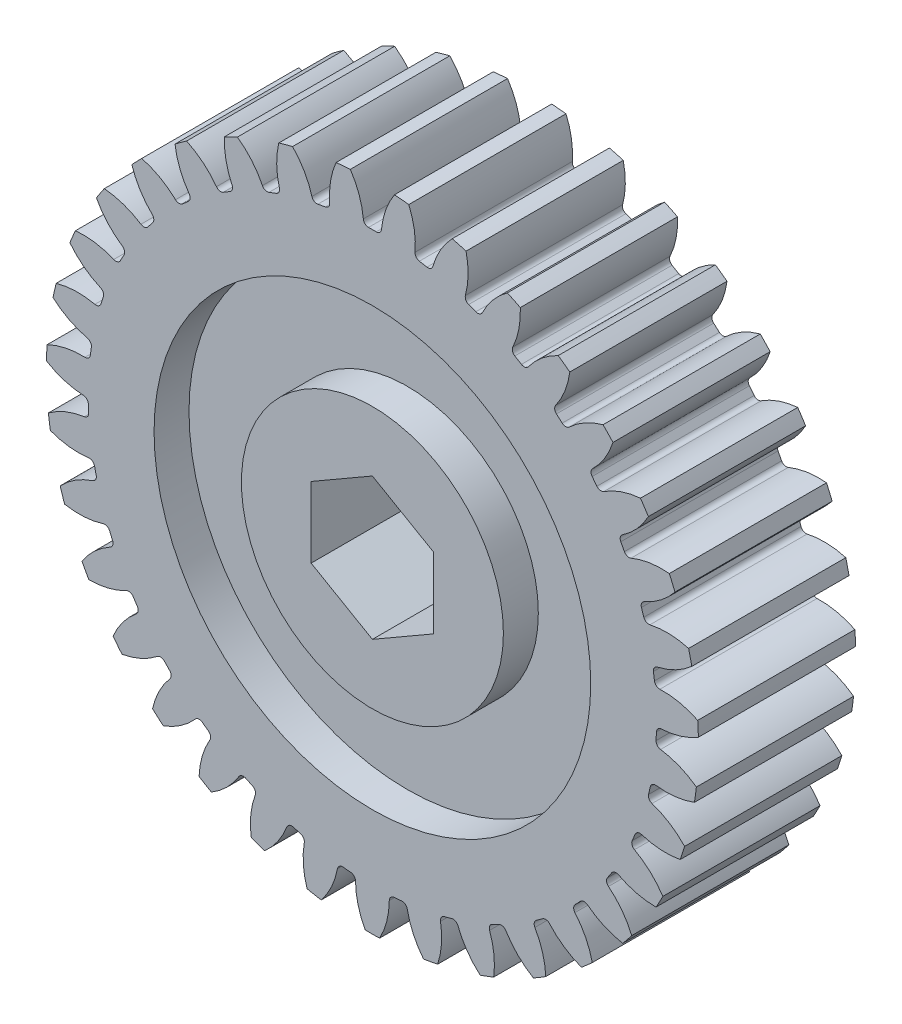
SolidWorks part; units mm, degrees
ref_plane "Ebene vorne" through (0, 0, 0) normal (0, 0, 1) x (1, 0, 0)
ref_plane "Ebene oben" through (0, 0, 0) normal (0, 1, 0) x (1, 0, 0)
ref_plane "Ebene rechts" through (0, 0, 0) normal (1, 0, 0) x (0, 0, -1)
sketch "Skizze1" plane through (0, 0, 0) normal (0, 0, 1) x (1, 0, 0)
  circle A0 centre (0, 0) radius 18.6665
  dimension "D1" = 37.333
extrude "Aufsatz-Linear austragen1" add sketch "Skizze1" along normal mid plane 9
sketch "Skizze4" plane through (0, 0, 4.5) normal (0, 0, 1) x (1, 0, 0)
  circle A0 centre (0, 0) radius 7.5
  circle A1 centre (0, 0) radius 12.5
  dimension "D1" = 25
  dimension "D2" = 15
extrude "Schnitt-Linear austragen2" cut sketch "Skizze4" against normal blind 2
sketch "Skizze6" plane through (0, 0, 4.5) normal (0, 0, 1) x (1, 0, 0)
  line L0 (0, 0) -> (0, 18.6665) construction
  line L1 (-0.2199, 16.267) -> (0.2199, 16.267)
  circle A0 centre (0, 0) radius 18.6665 construction
  arc A1 (0.5184, 16.5377) -> (2.08, 19.547) centre (5.0567, 16.0926) cw
  arc A2 (-0.5184, 16.5377) -> (-2.08, 19.547) centre (-5.0567, 16.0926) ccw
  arc A3 (-2.08, 19.547) -> (2.08, 19.547) centre (0, 1.6676) cw
  arc A4 (0.2199, 16.267) -> (0.5184, 16.5377) centre (0.2199, 16.567) ccw
  arc A5 (-0.5184, 16.5377) -> (-0.2199, 16.267) centre (-0.2199, 16.567) ccw
  point P13 (0, 16.267)
  point P16 (0.5, 16.267)
  point P19 (-0.5, 16.267)
  dimension "D5" = 4.56
  dimension "D6" = 18
  dimension "D7" = 0.3
  dimension "D1" = 0.5
  dimension "D2" = 16.267
  dimension "D3" = 1.58
  dimension "D4" = 3.28
extrude "Schnitt-Linear austragen3" cut sketch "Skizze6" against normal through all
pattern_circular "Kreismuster1" count 35 over 360 about axis through (0, 0, 0) along (0, 0, 1) of "Schnitt-Linear austragen3"
sketch "Skizze8" plane through (0, 0, -4.5) normal (0, 0, -1) x (-1, 0, 0)
  circle A0 centre (0, 0) radius 6
extrude "Aufsatz-Linear austragen2" add sketch "Skizze8" along normal blind 1 contours A0
sketch "Skizze7" plane through (0, 0, 4.5) normal (0, 0, 1) x (1, 0, 0)
  line L1 (0, 4.05) -> (-3.5074, 2.025)
  line L2 (-3.5074, 2.025) -> (-3.5074, -2.025)
  line L3 (-3.5074, -2.025) -> (0, -4.05)
  line L4 (0, -4.05) -> (3.5074, -2.025)
  line L5 (3.5074, -2.025) -> (3.5074, 2.025)
  line L6 (3.5074, 2.025) -> (0, 4.05)
  circle A0 centre (0, 0) radius 3.5074 construction
  dimension "D1" = 8.1
extrude "Schnitt-Linear austragen4" cut sketch "Skizze7" against normal through all
